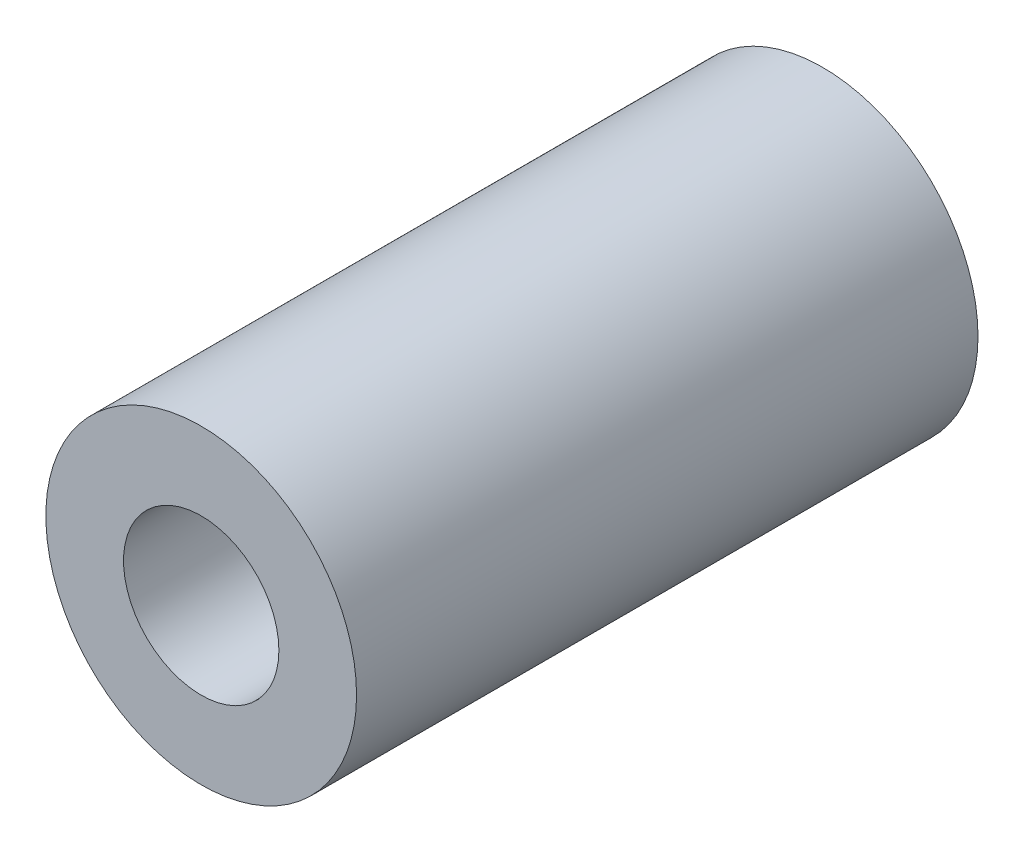
SolidWorks part; units mm, degrees
ref_plane "Front Plane" through (0, 0, 0) normal (0, 0, 1) x (1, 0, 0)
ref_plane "Top Plane" through (0, 0, 0) normal (0, 1, 0) x (1, 0, 0)
ref_plane "Right Plane" through (0, 0, 0) normal (1, 0, 0) x (0, 0, -1)
sketch "Sketch1" plane through (0, 0, 0) normal (0, 0, 1) x (1, 0, 0)
  circle A0 centre (0, 0) radius 5
  circle A2 centre (0, 0) radius 10
  dimension "D1" = 10
  dimension "D3" = 20
extrude "Boss-Extrude1" add sketch "Sketch1" along normal mid plane 40
sketch "Sketch2" plane through (0, 0, 20) normal (0, 0, 1) x (1, 0, 0)
  line L1 (0, 10) -> (0, 15.1104)
  circle A0 centre (0, 0) radius 10
  circle A1 centre (0.1418, 0.111) radius 15
  dimension "D1" = 20
